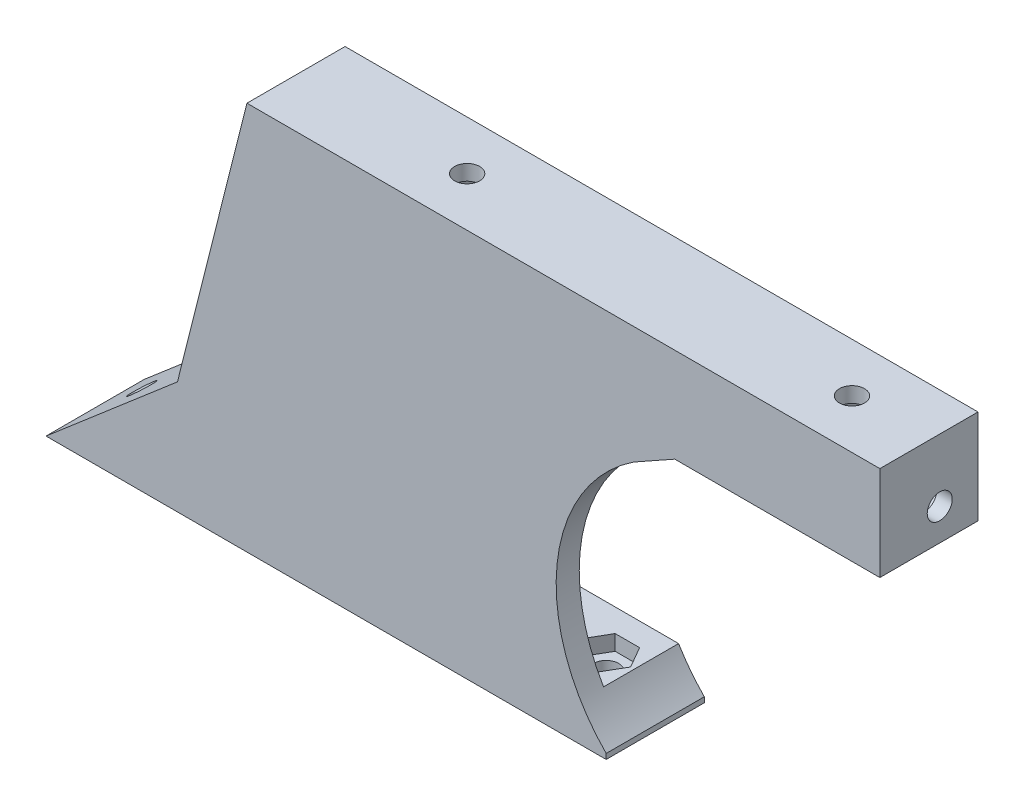
SolidWorks part; units mm, degrees
ref_plane "Alzado" through (0, 0, 0) normal (0, 0, 1) x (1, 0, 0)
ref_plane "Planta" through (0, 0, 0) normal (0, 1, 0) x (1, 0, 0)
ref_plane "Vista lateral" through (0, 0, 0) normal (1, 0, 0) x (0, 0, -1)
sketch "Croquis1" plane through (0, 0, 0) normal (0, 0, 1) x (1, 0, 0)
  line L3 (-46.6759, 50.5119) -> (-55.7, 14.6421)
  line L6 (-55.7, 14.6421) -> (-72.7832, 0)
  line L7 (-72.7832, 0) -> (0, 0)
  line L8 (0, 0) -> (0, 0.6807)
  line L9 (8.9133, 38.25) -> (3.5627, 35.25)
  line L10 (8.9133, 38.25) -> (35.5627, 38.25)
  line L11 (35.5627, 38.25) -> (35.5627, 50.5119)
  line L12 (-46.6759, 50.5119) -> (35.5627, 50.5119)
  arc A0 (3.5627, 35.25) -> (0, 0.6807) centre (16, 16.5) ccw
  dimension "D1" = 22.5
extrude "Saliente-Extruir1" add sketch "Croquis1" against normal blind 3
sketch "Croquis2" plane through (0, 0, -3) normal (0, 0, -1) x (-1, 0, 0)
  line L0 (42.5264, 46.5119) -> (51.239, 11.8804)
  line L2 (-35.5627, 38.25) -> (-35.5627, 50.5119) construction
  line L3 (-35.5627, 50.5119) -> (46.6759, 50.5119) construction
  line L4 (-8.9133, 38.25) -> (-35.5627, 38.25) construction
  line L6 (-35.5627, 50.5119) -> (-35.5627, 38.25)
  line L7 (-35.5627, 38.25) -> (-31.5627, 38.25)
  line L9 (-31.5627, 50.5119) -> (-31.5627, 46.5119) construction
  line L10 (-31.5627, 38.25) -> (-31.5627, 46.5119)
  line L11 (-31.5627, 46.5119) -> (42.5264, 46.5119)
  line L12 (-35.5627, 50.5119) -> (46.6759, 50.5119)
  line L13 (46.6759, 50.5119) -> (55.7, 14.6421)
  line L14 (55.7, 14.6421) -> (72.7832, 0)
  line L15 (72.7832, 0) -> (0, 0)
  line L16 (0, 0) -> (0, 0.6807)
  line L17 (36.3916, 0) -> (36.3916, 5) construction
  line L18 (3.3391, 5) -> (59.2664, 5)
  line L21 (51.239, 11.8804) -> (59.2664, 5)
  arc A0 (0, 0.6807) -> (-3.5627, 35.25) centre (-16, 16.5) ccw construction
  arc A1 (0, 0.6807) -> (3.3391, 5) centre (-16, 16.5) ccw
  dimension "D1" = 4
  dimension "D2" = 38.9017
  dimension "D3" = 78.0891
  dimension "D4" = 86.8016
  dimension "D5" = 94.8291
  dimension "D6" = 38.6316
extrude "Saliente-Extruir2" add sketch "Croquis2" along normal blind 9.75
sketch "Croquis4" plane through (0, 0, 0) normal (0, -1, 0) x (1, 0, 0)
  circle A0 centre (-7, -7) radius 1.625
  circle A1 centre (-52.7832, -7) radius 1.625
  dimension "D1" = 3.25
extrude "Cortar-Extruir1" cut sketch "Croquis4" against normal up to vertex (5 mm away)
sketch "Croquis5" plane through (0, 5, 0) normal (0, 1, 0) x (1, 0, 0)
  line L1 (-10.18, 7) -> (-8.59, 4.246)
  line L2 (-8.59, 4.246) -> (-5.41, 4.246)
  line L3 (-5.41, 4.246) -> (-3.82, 7)
  line L4 (-3.82, 7) -> (-5.41, 9.754)
  line L5 (-5.41, 9.754) -> (-8.59, 9.754)
  line L6 (-8.59, 9.754) -> (-10.18, 7)
  line L7 (-49.6032, 7) -> (-51.1932, 9.754)
  line L8 (-51.1932, 9.754) -> (-54.3732, 9.754)
  line L9 (-54.3732, 9.754) -> (-55.9632, 7)
  line L10 (-55.9632, 7) -> (-54.3732, 4.246)
  line L11 (-54.3732, 4.246) -> (-51.1932, 4.246)
  line L12 (-51.1932, 4.246) -> (-49.6032, 7)
  circle A0 centre (-7, 7) radius 2.754 construction
  circle A1 centre (-52.7832, 7) radius 2.754 construction
  dimension "D1" = 5.5079
extrude "Cortar-Extruir2" cut sketch "Croquis5" against normal blind 2
sketch "Croquis6" plane through (-30.8242, 35.9632, 0) normal (-0.6508, 0.7593, 0) x (0.7593, 0.6508, 0)
  line L1 (-55.2622, 6.375) -> (-32.7627, 6.375) construction
  line L2 (-55.2622, 12.75) -> (-55.2622, 0) construction
  line L3 (-32.7627, 12.75) -> (-32.7627, 0) construction
  line L4 (-47.2622, 0) -> (-47.2622, 12.75) construction
  line L5 (-55.2622, 12.75) -> (-32.7627, 12.75) construction
  circle A0 centre (-47.2622, 6.375) radius 1.625
  dimension "D1" = 3.25
extrude "Cortar-Extruir3" cut sketch "Croquis6" against normal blind 9
sketch "Croquis9" plane through (-30.8242, 35.9632, 0) normal (-0.6508, 0.7593, 0) x (0.7593, 0.6508, 0)
  line L1 (-50.4322, 6.375) -> (-48.8472, 3.6297)
  line L2 (-48.8472, 3.6297) -> (-45.6772, 3.6297)
  line L3 (-45.6772, 3.6297) -> (-44.0922, 6.375)
  line L4 (-44.0922, 6.375) -> (-45.6772, 9.1203)
  line L5 (-45.6772, 9.1203) -> (-48.8472, 9.1203)
  line L6 (-48.8472, 9.1203) -> (-50.4322, 6.375)
  circle A0 centre (-47.2622, 6.375) radius 2.7453 construction
  dimension "D1" = 5.4906
extrude "Cortar-Extruir4" cut sketch "Croquis9" against normal blind 10
sketch "Croquis10" plane through (-30.8242, 35.9632, 0) normal (-0.6508, 0.7593, 0) x (0.7593, 0.6508, 0)
  line L0 (-50.4322, 6.375) -> (-44.0922, 6.375) construction
  line L1 (-47.2622, 3.6297) -> (-47.2622, 9.1203) construction
  line L2 (-48.8472, 3.6297) -> (-45.6772, 3.6297) construction
  line L3 (-45.6772, 9.1203) -> (-48.8472, 9.1203) construction
  line L5 (-50.4322, 6.375) -> (-48.8472, 3.6297)
  line L6 (-48.8472, 3.6297) -> (-45.6772, 3.6297)
  line L7 (-45.6772, 3.6297) -> (-44.0922, 6.375)
  line L8 (-44.0922, 6.375) -> (-45.6772, 9.1203)
  line L9 (-45.6772, 9.1203) -> (-48.8472, 9.1203)
  line L10 (-48.8472, 9.1203) -> (-50.4322, 6.375)
  circle A0 centre (-47.2622, 6.375) radius 1.625
  circle A1 centre (-47.2622, 6.375) radius 2.7453 construction
  dimension "D1" = 3.25
extrude "Saliente-Extruir3" add sketch "Croquis10" against normal blind 2
sketch "Croquis13" plane through (-55.8489, 14.0503, 0) normal (-0.9698, 0.244, 0) x (0, 0, 1)
  line L0 (-6.375, 19.104) -> (-6.375, 28.3508) construction
  line L1 (-6.375, 28.3508) -> (-6.375, 37.5977) construction
  line L2 (-12.75, 37.5977) -> (0, 37.5977) construction
  line L4 (-6.375, 20.5474) -> (-3.621, 22.1374)
  line L5 (-3.621, 22.1374) -> (-3.621, 25.3174)
  line L6 (-3.621, 25.3174) -> (-6.375, 26.9074)
  line L7 (-6.375, 26.9074) -> (-9.129, 25.3174)
  line L8 (-9.129, 25.3174) -> (-9.129, 22.1374)
  line L9 (-9.129, 22.1374) -> (-6.375, 20.5474)
  circle A2 centre (-6.375, 23.7274) radius 2.754 construction
  dimension "D1" = 10.6903
  dimension "D2" = 5.5079
extrude "Cortar-Extruir5" cut sketch "Croquis13" against normal up to vertex (5 mm away)
sketch "Croquis14" plane through (-55.8489, 14.0503, 0) normal (-0.9698, 0.244, 0) x (0, 0, 1)
  line L0 (-6.375, 26.9074) -> (-6.375, 20.5474) construction
  line L2 (-6.375, 26.9074) -> (-9.129, 25.3174)
  line L3 (-9.129, 25.3174) -> (-9.129, 22.1374)
  line L4 (-9.129, 22.1374) -> (-6.375, 20.5474)
  line L5 (-6.375, 20.5474) -> (-3.621, 22.1374)
  line L6 (-3.621, 22.1374) -> (-3.621, 25.3174)
  line L7 (-3.621, 25.3174) -> (-6.375, 26.9074)
  circle A0 centre (-6.375, 23.7274) radius 2.754 construction
  circle A1 centre (-6.375, 23.7274) radius 1.625
  dimension "D1" = 3.25
extrude "Saliente-Extruir4" add sketch "Croquis14" against normal blind 3
sketch "Croquis15" plane through (0, 50.5119, 0) normal (0, 1, 0) x (1, 0, 0)
  line L2 (35.5627, 0) -> (-46.6759, 0) construction
  line L4 (35.5627, 12.75) -> (35.5627, 0) construction
  circle A2 centre (25.5627, 6.375) radius 1.625
  circle A3 centre (-24.4373, 6.375) radius 1.625
  dimension "D1" = 3.25
  dimension "D2" = 10
  dimension "D3" = 60
  dimension "D4" = 6.375
extrude "Cortar-Extruir6" cut sketch "Croquis15" against normal up to vertex (4 mm away)
sketch "Croquis16" plane through (0, 46.5119, 0) normal (0, -1, 0) x (1, 0, 0)
  line L1 (22.3827, -6.375) -> (23.9727, -9.129)
  line L2 (23.9727, -9.129) -> (27.1527, -9.129)
  line L3 (27.1527, -9.129) -> (28.7427, -6.375)
  line L4 (28.7427, -6.375) -> (27.1527, -3.621)
  line L5 (27.1527, -3.621) -> (23.9727, -3.621)
  line L6 (23.9727, -3.621) -> (22.3827, -6.375)
  line L7 (-21.2573, -6.375) -> (-22.8473, -3.621)
  line L8 (-22.8473, -3.621) -> (-26.0273, -3.621)
  line L9 (-26.0273, -3.621) -> (-27.6173, -6.375)
  line L10 (-27.6173, -6.375) -> (-26.0273, -9.129)
  line L11 (-26.0273, -9.129) -> (-22.8473, -9.129)
  line L12 (-22.8473, -9.129) -> (-21.2573, -6.375)
  circle A0 centre (25.5627, -6.375) radius 2.754 construction
  circle A1 centre (-24.4373, -6.375) radius 2.754 construction
  dimension "D1" = 5.5079
extrude "Cortar-Extruir7" cut sketch "Croquis16" against normal blind 2
sketch "Croquis17" plane through (35.5627, 0, 0) normal (1, 0, 0) x (0, 0, -1)
  circle A0 centre (7.7775, 42.38) radius 1.625
  dimension "D1" = 3.25
extrude "Cortar-Extruir9" cut sketch "Croquis17" against normal up to vertex (4 mm away)
sketch "Croquis18" plane through (31.5627, 0, 0) normal (-1, 0, 0) x (0, 0, 1)
  line L1 (-7.7775, 39.2) -> (-5.0235, 40.79)
  line L2 (-5.0235, 40.79) -> (-5.0235, 43.97)
  line L3 (-5.0235, 43.97) -> (-7.7775, 45.56)
  line L4 (-7.7775, 45.56) -> (-10.5315, 43.97)
  line L5 (-10.5315, 43.97) -> (-10.5315, 40.79)
  line L6 (-10.5315, 40.79) -> (-7.7775, 39.2)
  circle A0 centre (-7.7775, 42.38) radius 2.754 construction
  dimension "D1" = 5.5079
extrude "Cortar-Extruir10" cut sketch "Croquis18" against normal blind 2
